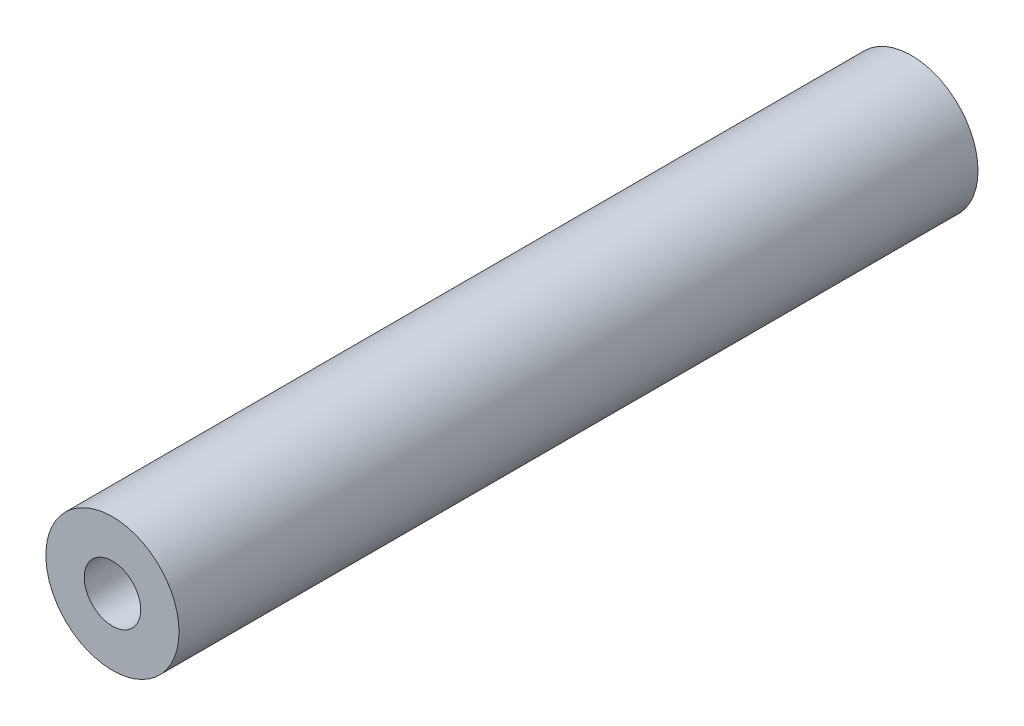
SolidWorks part; units mm, degrees
material "6061-T6 (SS)"
ref_plane "Front Plane" through (0, 0, 0) normal (0, 0, 1) x (1, 0, 0)
ref_plane "Top Plane" through (0, 0, 0) normal (0, 1, 0) x (1, 0, 0)
ref_plane "Right Plane" through (0, 0, 0) normal (1, 0, 0) x (0, 0, -1)
sketch "Sketch1" plane through (0, 0, 0) normal (0, 0, 1) x (1, 0, 0)
  circle A0 centre (0, 0) radius 2.0193
  circle A1 centre (0, 0) radius 4.7625
  dimension "D1" = 4.0386
  dimension "D2" = 9.525
extrude "Boss-Extrude1" add sketch "Sketch1" along normal blind 57.15
